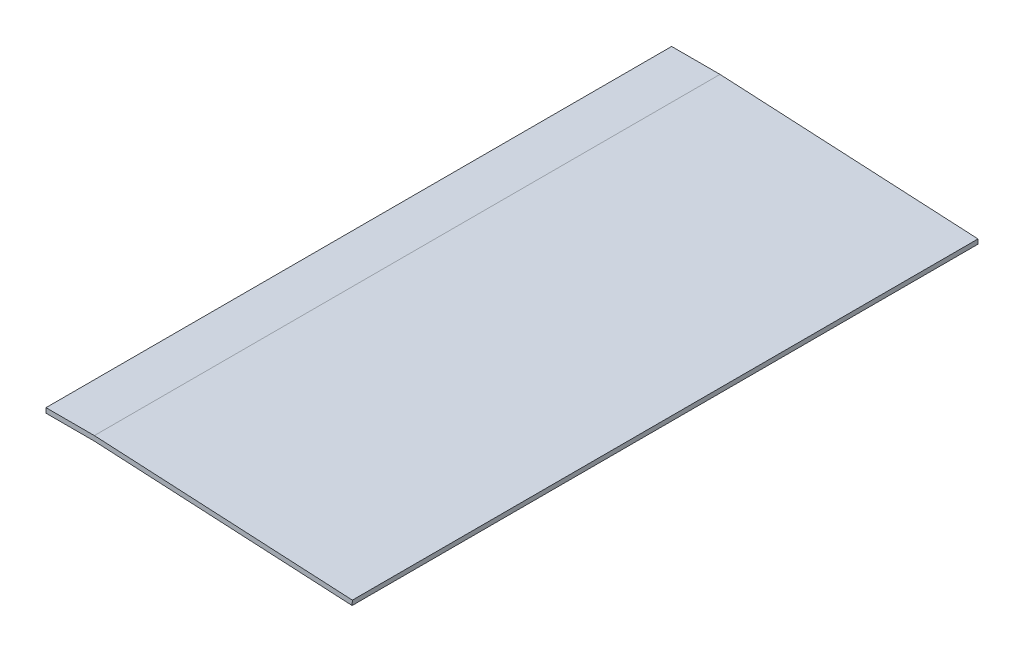
SolidWorks part; units mm, degrees
ref_plane "Front Plane" through (0, 0, 0) normal (0, 0, 1) x (1, 0, 0)
ref_plane "Top Plane" through (0, 0, 0) normal (0, 1, 0) x (1, 0, 0)
ref_plane "Right Plane" through (0, 0, 0) normal (1, 0, 0) x (0, 0, -1)
sketch "Sketch2" plane through (0, 0, 0) normal (0, 0, 1) x (1, 0, 0)
  line L0 (0, 0) -> (0, 3)
  line L1 (0, 3) -> (30, 3)
  line L2 (30, 3) -> (30, 0)
  line L3 (30, 0) -> (0, 0)
  line L4 (30, 0) -> (189.843, -8.377)
  line L5 (189.843, -8.377) -> (190, -5.3811)
  line L6 (190, -5.3811) -> (30, 3)
  dimension "D1" = 3
  dimension "D2" = 30
  dimension "D3" = 3
  dimension "D4" = 160
  dimension "D5" = 177
extrude "Boss-Extrude1" add sketch "Sketch2" along normal blind 388 contours L3 L2 L1 L0 | L5 L6 L2 L4
